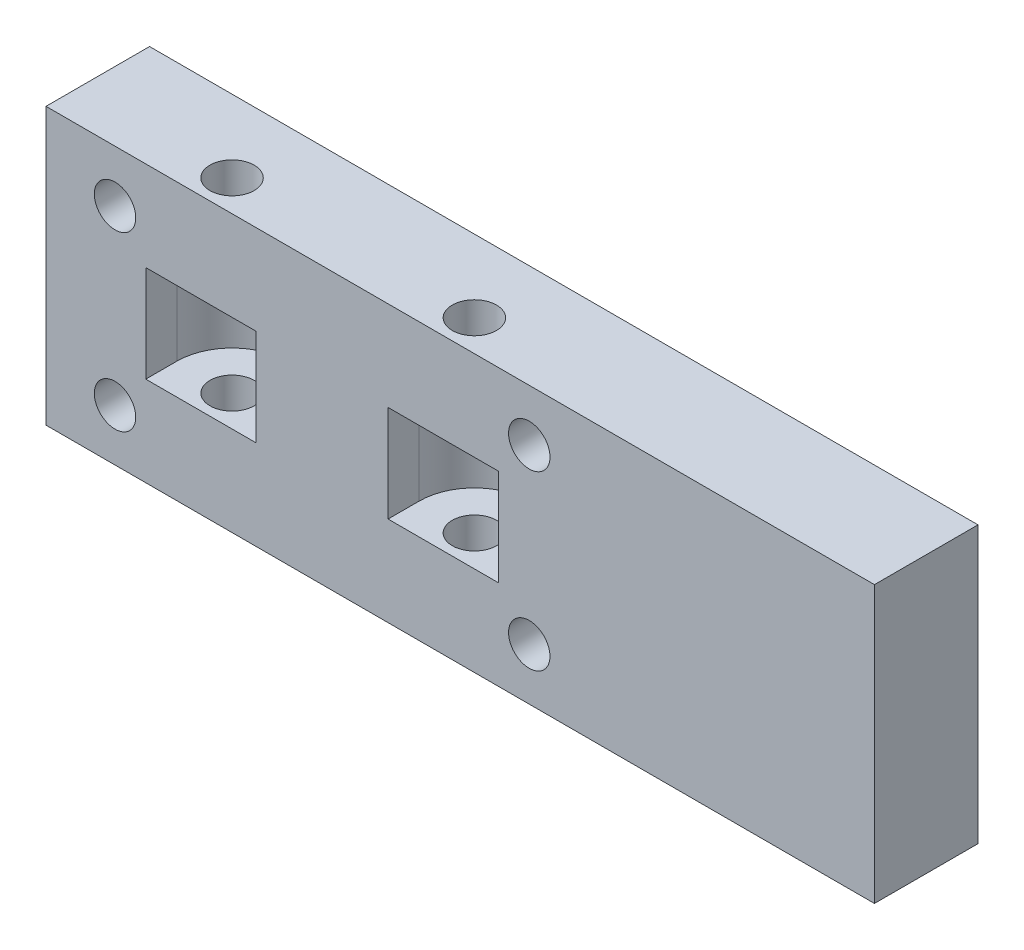
SolidWorks part; units mm, degrees
ref_plane "Front Plane" through (0, 0, 0) normal (0, 0, 1) x (1, 0, 0)
ref_plane "Top Plane" through (0, 0, 0) normal (0, 1, 0) x (1, 0, 0)
ref_plane "Right Plane" through (0, 0, 0) normal (1, 0, 0) x (0, 0, -1)
sketch "Sketch1" plane through (0, 0, 0) normal (0, 0, 1) x (1, 0, 0)
  line L2 (-38.1, -12.7) -> (-38.1, 12.7)
  line L3 (-38.1, 12.7) -> (38.1, 12.7)
  line L10 (38.1, -12.7) -> (38.1, 12.7)
  line L11 (-38.1, -12.7) -> (38.1, -12.7)
  line L14 (-38.1, 12.7) -> (38.1, -12.7) construction
  point P2 (0, 0)
  dimension "D1" = 76.2
  dimension "D2" = 25.4
extrude "Boss-Extrude1" add sketch "Sketch1" along normal blind 9.525
sketch "Sketch4" plane through (0, 0, 0) normal (0, 1, 0) x (1, 0, 0)
  line L7 (38.1, -9.525) -> (-38.1, -9.525) construction
  line L8 (-28.9242, -6.6675) -> (-28.9242, -9.525)
  line L9 (-18.7643, -6.6675) -> (-18.7642, -9.525)
  line L10 (-18.7642, -9.525) -> (-28.9242, -9.525)
  line L11 (-38.1, -9.525) -> (-38.1, 0) construction
  arc A2 (-18.7643, -6.6675) -> (-28.9242, -6.6675) centre (-23.8442, -6.6675) ccw
  point P1 (8.89, -9.525)
  dimension "D1" = 10.16
  dimension "D2" = 2.8575
  dimension "D3" = 14.2558
extrude "Cut-Extrude2" cut sketch "Sketch4" against normal mid plane 8.89
ref_plane "Plane3" through (-12.7, 0, 0) normal (-1, 0, 0) x (0, 0, 1)
sketch "Sketch2" plane through (0, 0, 9.525) normal (0, 0, 1) x (1, 0, 0)
  line L0 (-38.1, -12.7) -> (38.1, -12.7) construction
  line L1 (-38.1, 12.7) -> (-38.1, -12.7) construction
  circle A0 centre (-31.75, 7.9375) radius 1.905
  dimension "D1" = 3.81
  dimension "D2" = 20.6375
  dimension "D3" = 6.35
extrude "Cut-Extrude1" cut sketch "Sketch2" against normal through all
sketch "Sketch5" plane through (0, 12.7, 0) normal (0, 1, 0) x (1, 0, 0)
  line L0 (38.1, -9.525) -> (-38.1, -9.525) construction
  line L1 (-38.1, -9.525) -> (-38.1, 0) construction
  circle A0 centre (-23.8442, -6.6675) radius 2.032
  dimension "D3" = 4.064
  dimension "D1" = 2.8575
  dimension "D2" = 14.2558
extrude "Cut-Extrude3" cut sketch "Sketch5" against normal blind 28.575
mirror "Mirror1" about plane through (0, 0, 0) normal (0, 1, 0) of "Cut-Extrude1"
mirror "Mirror2" about plane through (-12.7, 0, 0) normal (-1, 0, 0) of "Cut-Extrude2", "Cut-Extrude1", "Cut-Extrude3", "Mirror1"
